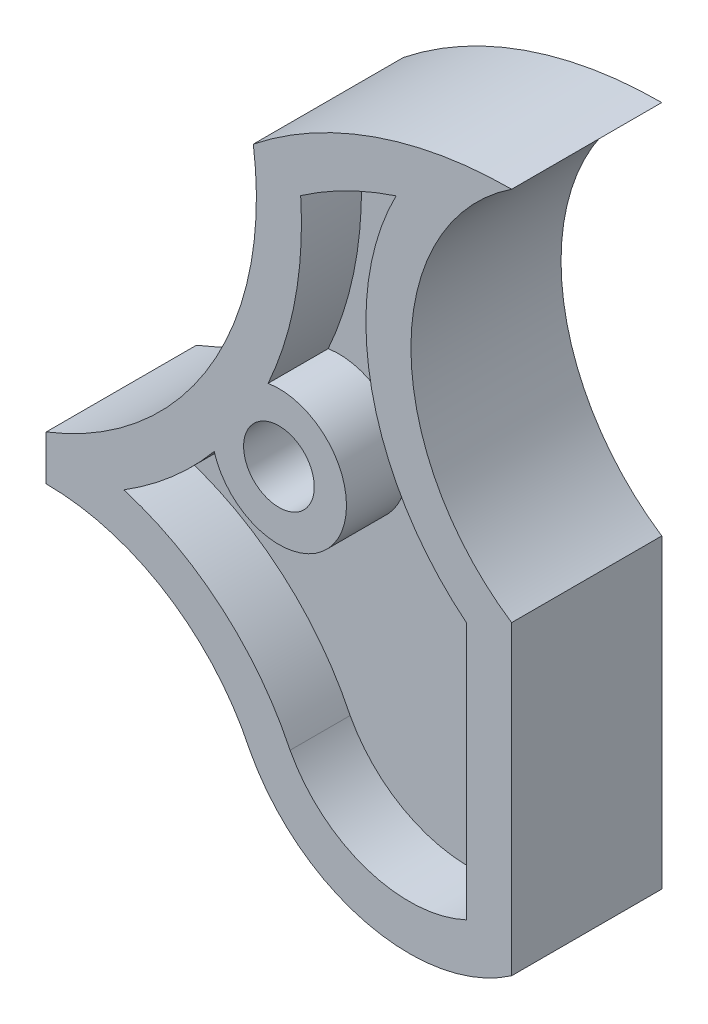
SolidWorks part; units mm, degrees
ref_plane "Alzado" through (0, 0, 0) normal (0, 0, 1) x (1, 0, 0)
ref_plane "Planta" through (0, 0, 0) normal (0, 1, 0) x (1, 0, 0)
ref_plane "Vista lateral" through (0, 0, 0) normal (1, 0, 0) x (0, 0, -1)
sketch "Croquis1" plane through (0, 0, 0) normal (0, 0, 1) x (1, 0, 0)
  line L1 (-15.5, -23.75) -> (15.5, -23.75)
  line L2 (-15.5, -23.75) -> (-15.5, 23.75)
  line L3 (-15.5, 23.75) -> (15.5, 23.75)
  line L4 (15.5, -23.75) -> (15.5, 23.75)
  line L5 (-15.5, -23.75) -> (15.5, 23.75) construction
  line L6 (-15.5, 23.75) -> (15.5, -23.75) construction
  circle A0 centre (0, 0) radius 1.5
  dimension "D1" = 3
  dimension "D2" = 47.5
  dimension "D3" = 31
extrude "Saliente-Extruir1" add sketch "Croquis1" along normal mid plane 10
sketch "Croquis2" plane through (0, 0, 5) normal (0, 0, 1) x (1, 0, 0)
  line L0 (-15.5, -8.75) -> (63.2071, -8.75) construction
  line L4 (15.5, -23.75) -> (15.5, 23.75)
  line L5 (15.5, 23.75) -> (-15.5, 23.75)
  line L6 (-15.5, 23.75) -> (-15.5, -23.75)
  line L7 (-15.5, -23.75) -> (15.5, -23.75)
  line L8 (15.5, -23.75) -> (15.5, 23.75)
  line L9 (15.5, 23.75) -> (-15.5, 23.75)
  line L10 (-15.5, 23.75) -> (-15.5, -23.75)
  line L11 (-15.5, -23.75) -> (15.5, -23.75)
  circle A0 centre (-15.5, -23.75) radius 15
  arc A1 (-1.9396, -17.3378) -> (15.5, -21.6236) centre (8.68, -11.75) ccw
  arc A2 (15.5, 23.75) -> (15.5, -1.25) centre (23.7916, 11.25) ccw
  arc A3 (-15.5, -5.75) -> (-1.7063, 17.75) centre (-23.5, 14.7439) ccw
  arc A4 (-1.7063, 17.75) -> (15.5, 23.75) centre (15.5, -3.9215) cw
  point P16 (-19.9095, 20.7308)
  point P17 (17.2927, 5.9345)
  point P18 (-18.782, 18.7538)
  point P19 (0, 0)
  point P20 (15.5, 5.8445)
  point P21 (0, 0)
  point P22 (-1.9396, 17.75)
  point P23 (-1.9396, 17.75)
  line M5 (15.5, -23.75) -> (15.5, 23.75)
  line M6 (15.5, 23.75) -> (-15.5, 23.75)
  line M7 (-15.5, 23.75) -> (-15.5, -23.75)
  line M8 (-15.5, -23.75) -> (15.5, -23.75)
  dimension "D2" = 30
  dimension "D3" = 25
  dimension "D4" = 15
  dimension "D5" = 12
  dimension "D9" = 22
  dimension "D6" = 6.82
  dimension "D7" = 3
  dimension "D8" = 6
  dimension "D10" = 8
  dimension "D1" = 0
extrude "Cortar-Extruir1" cut sketch "Croquis2" against normal blind 10 contours A0 L10 M8 | A1 A0 L11 | A1 M8 M5 | A3 A4 M6 M7 | A2 M5
sketch "Croquis4" plane through (0, 0, 5) normal (0, 0, 1) x (1, 0, 0)
  line L2 (15.5, -21.6236) -> (15.5, -1.25)
  line L3 (-15.5, -5.75) -> (-15.5, -8.75)
  line L4 (15.5, -21.6236) -> (15.5, -1.25)
  line L5 (-15.5, -5.75) -> (-15.5, -8.75)
  line L8 (12.5, -19.8991) -> (12.5, -2.7679)
  line L9 (12.5, -19.8991) -> (12.5, -2.7679)
  arc A5 (-1.9396, -17.3378) -> (15.5, -21.6236) centre (8.68, -11.75) ccw
  arc A6 (15.5, 23.75) -> (15.5, -1.25) centre (23.7916, 11.25) ccw
  arc A7 (15.5, 23.75) -> (-1.7063, 17.75) centre (15.5, -3.9215) ccw
  arc A8 (-15.5, -5.75) -> (-1.7063, 17.75) centre (-23.5, 14.7439) ccw
  arc A9 (-1.9396, -17.3378) -> (-15.5, -8.75) centre (-15.5, -23.75) ccw
  arc A10 (-1.9396, -17.3378) -> (15.5, -21.6236) centre (8.68, -11.75) ccw
  arc A11 (15.5, 23.75) -> (15.5, -1.25) centre (23.7916, 11.25) ccw
  arc A12 (15.5, 23.75) -> (-1.7063, 17.75) centre (15.5, -3.9215) ccw
  arc A13 (-15.5, -5.75) -> (-1.7063, 17.75) centre (-23.5, 14.7439) ccw
  arc A14 (-1.9396, -17.3378) -> (-15.5, -8.75) centre (-15.5, -23.75) ccw
  arc A20 (0.7418, -15.9908) -> (12.5, -19.8991) centre (8.68, -11.75) ccw
  arc A21 (7.8032, 19.5187) -> (12.5, -2.7679) centre (23.7916, 11.25) ccw
  arc A22 (7.8032, 19.5187) -> (1.4479, 16.3571) centre (15.5, -3.9215) ccw
  arc A23 (-10.3328, -6.5076) -> (1.4479, 16.3571) centre (-23.5, 14.7439) ccw
  arc A24 (0.7418, -15.9908) -> (-10.3328, -6.5076) centre (-15.5, -23.75) ccw
  arc A25 (0.7418, -15.9908) -> (12.5, -19.8991) centre (8.68, -11.75) ccw
  arc A26 (7.8032, 19.5187) -> (12.5, -2.7679) centre (23.7916, 11.25) ccw
  arc A27 (7.8032, 19.5187) -> (1.4479, 16.3571) centre (15.5, -3.9215) ccw
  arc A28 (-10.3328, -6.5076) -> (1.4479, 16.3571) centre (-23.5, 14.7439) ccw
  arc A29 (0.7418, -15.9908) -> (-10.3328, -6.5076) centre (-15.5, -23.75) ccw
  circle M21 centre (0, 0) radius 1.5
  dimension "D1" = 0
  dimension "D2" = 3
extrude "Cortar-Extruir2" cut sketch "Croquis4" against normal blind 4 contours A29 A25 L9 A26 A27 A28 M21
mirror "Simetría1" about plane through (0, 0, 0) normal (0, 0, 1) of "Cortar-Extruir2"
sketch "Croquis5" plane through (0, 0, 1) normal (0, 0, 1) x (1, 0, 0)
  circle A0 centre (0, 0) radius 1.5 construction
  circle A1 centre (0, 0) radius 1.5
  circle A2 centre (0, 0) radius 2.355
  circle A3 centre (0, 0) radius 4.5
  arc M6 (1.4479, 16.3571) -> (-10.3328, -6.5076) centre (-23.5, 14.7439) cw
  dimension "D1" = 4.71
  dimension "D2" = 9
extrude "Saliente-Extruir2" add sketch "Croquis5" along normal up to surface and the other way up to surface contours A3 A2 M6
